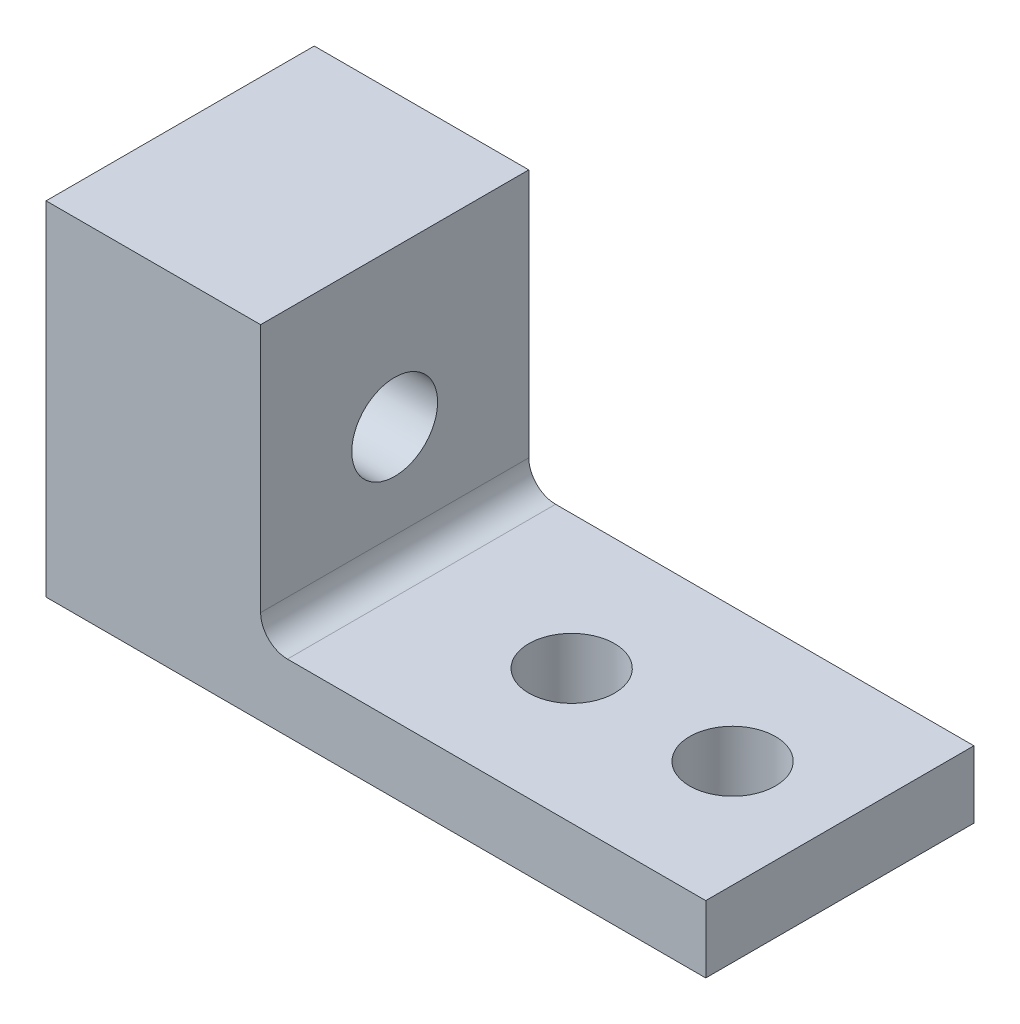
SolidWorks part; units mm, degrees
material "Plain Carbon Steel"
ref_plane "Front Plane" through (0, 0, 0) normal (0, 0, 1) x (1, 0, 0)
ref_plane "Top Plane" through (0, 0, 0) normal (0, 1, 0) x (1, 0, 0)
ref_plane "Right Plane" through (0, 0, 0) normal (1, 0, 0) x (0, 0, -1)
sketch "Sketch1" plane through (0, 0, 0) normal (0, 0, 1) x (1, 0, 0)
  line L0 (0, 0) -> (0, 16.256)
  line L1 (0, 16.256) -> (10.16, 16.256)
  line L2 (10.16, 16.256) -> (10.16, 3.175)
  line L3 (10.16, 3.175) -> (31.242, 3.175)
  line L4 (31.242, 3.175) -> (31.242, 0)
  line L5 (31.242, 0) -> (0, 0)
  dimension "D1" = 10.16
  dimension "D2" = 3.175
  dimension "D4" = 16.256
  dimension "D3" = 21.082
extrude "Boss-Extrude1" add sketch "Sketch1" against normal mid plane 12.7
sketch "Sketch2" plane through (0, 0, 0) normal (-1, 0, 0) x (0, 0, 1)
  circle A0 centre (0, 8.89) radius 2.032
  dimension "D1" = 4.064
  dimension "D2" = 8.89
extrude "Cut-Extrude1" cut sketch "Sketch2" against normal up to next
sketch "Sketch3" plane through (0, 0, 0) normal (0, -1, 0) x (1, 0, 0)
  circle A0 centre (18.542, 0) radius 2.032
  dimension "D1" = 4.064
  dimension "D2" = 8.382
extrude "Cut-Extrude2" cut sketch "Sketch3" against normal up to next
fillet "Fillet2" radius 1.27 1 edges at (10.16, 3.175, 0)
pattern_linear "LPattern1" count 2 spacing 7.62 along (1, 0, 0) of "Cut-Extrude2"
equation "\"D2@Sketch1\"=1/8"
